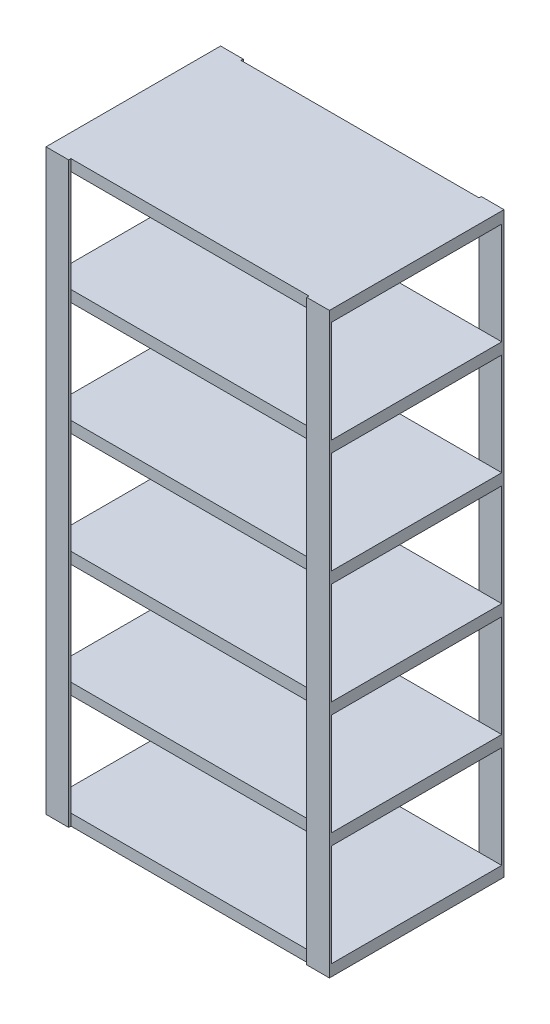
SolidWorks part; units mm, degrees
ref_plane "Ebene vorne" through (0, 0, 0) normal (0, 0, 1) x (1, 0, 0)
ref_plane "Ebene oben" through (0, 0, 0) normal (0, 1, 0) x (1, 0, 0)
ref_plane "Ebene rechts" through (0, 0, 0) normal (1, 0, 0) x (0, 0, -1)
sketch "Skizze1" plane through (0, 0, 0) normal (0, 1, 0) x (1, 0, 0)
  line L1 (-125, 75) -> (125, 75)
  line L2 (-125, 75) -> (-125, -75)
  line L3 (-125, -75) -> (125, -75)
  line L4 (125, 75) -> (125, -75)
  line L5 (-125, 75) -> (125, -75) construction
  line L6 (-125, -75) -> (125, 75) construction
  point P0 (0, 0)
  dimension "D1" = 250
  dimension "D2" = 150
extrude "Aufsatz-Linear austragen1" add sketch "Skizze1" along normal mid plane 10
sketch "Skizze2" plane through (0, 0, 75) normal (0, 0, 1) x (1, 0, 0)
  line L1 (-125, -5) -> (-105, -5)
  line L2 (-125, -5) -> (-125, 505)
  line L3 (-125, 505) -> (-105, 505)
  line L4 (-105, -5) -> (-105, 505)
  line L5 (125, -5) -> (105, -5)
  line L6 (125, -5) -> (125, 505)
  line L7 (125, 505) -> (105, 505)
  line L8 (105, -5) -> (105, 505)
  dimension "D1" = 20
  dimension "D2" = 20
  dimension "D3" = 510
  dimension "D4" = 510
extrude "Aufsatz-Linear austragen2" add sketch "Skizze2" along normal blind 2
sketch "Skizze3" plane through (0, 0, -75) normal (0, 0, -1) x (-1, 0, 0)
  line L1 (-125, -5) -> (-105, -5)
  line L2 (-125, -5) -> (-125, 505)
  line L3 (-125, 505) -> (-105, 505)
  line L4 (-105, -5) -> (-105, 505)
  line L5 (105, 505) -> (125, 505)
  line L6 (105, 505) -> (105, -5)
  line L7 (105, -5) -> (125, -5)
  line L8 (125, 505) -> (125, -5)
extrude "Aufsatz-Linear austragen3" add sketch "Skizze3" along normal blind 2
pattern_linear "Lineares Muster3" count 6 spacing 100 along (0, 1, 0) of "Aufsatz-Linear austragen1"
ref_plane "Ebene1" through (0, 100, 0) normal (0, 1, 0) x (1, 0, 0)
ref_plane "Ebene2" through (0, 200, 0) normal (0, 1, 0) x (1, 0, 0)
ref_plane "Ebene3" through (0, 300, 0) normal (0, 1, 0) x (1, 0, 0)
ref_plane "Ebene4" through (0, 400, 0) normal (0, 1, 0) x (1, 0, 0)
ref_plane "Ebene5" through (0, 500, 0) normal (0, 1, 0) x (1, 0, 0)
